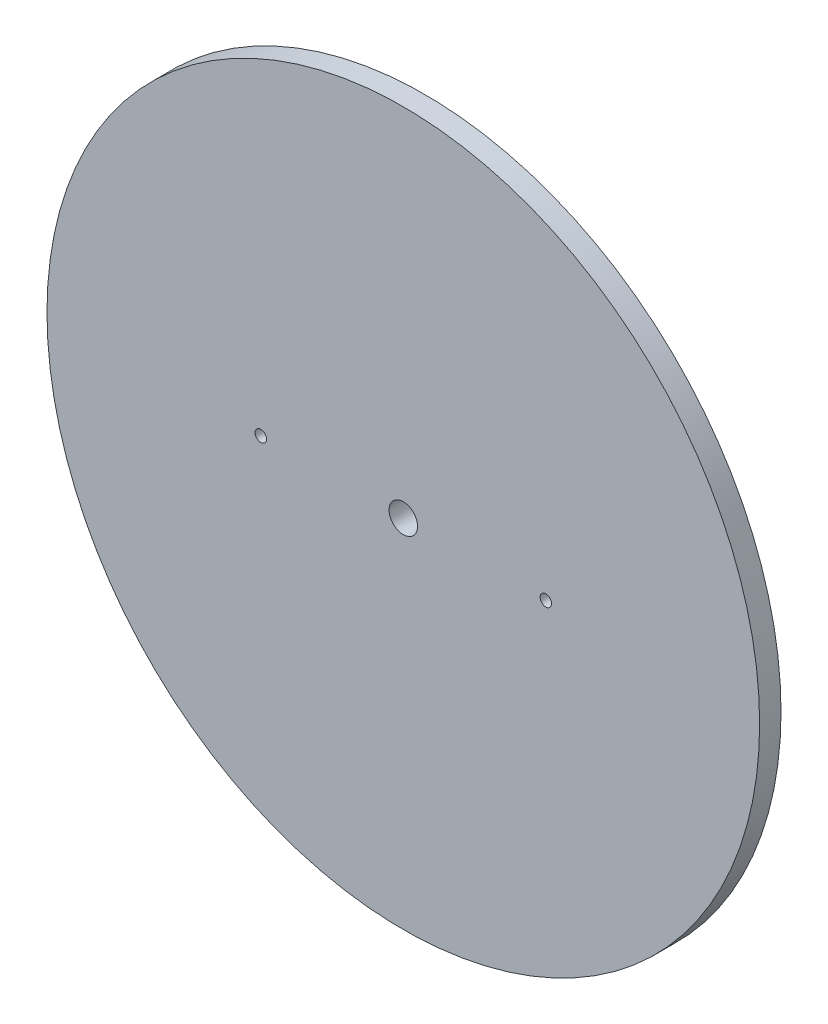
SolidWorks part; units mm, degrees
ref_plane "Front Plane" through (0, 0, 0) normal (0, 0, 1) x (1, 0, 0)
ref_plane "Top Plane" through (0, 0, 0) normal (0, 1, 0) x (1, 0, 0)
ref_plane "Right Plane" through (0, 0, 0) normal (1, 0, 0) x (0, 0, -1)
sketch "Sketch1" plane through (0, 0, 0) normal (0, 0, 1) x (1, 0, 0)
  circle A0 centre (0, 0) radius 100
extrude "Boss-Extrude1" add sketch "Sketch1" along normal blind 6
sketch "Sketch2" plane through (0, 0, 0) normal (0, 0, 1) x (1, 0, 0)
  circle A0 centre (0, 0) radius 4
  circle A1 centre (40, 0) radius 1.6
  circle A2 centre (-40, 0) radius 1.6
extrude "Cut-Extrude2" cut sketch "Sketch2" along normal blind 7
